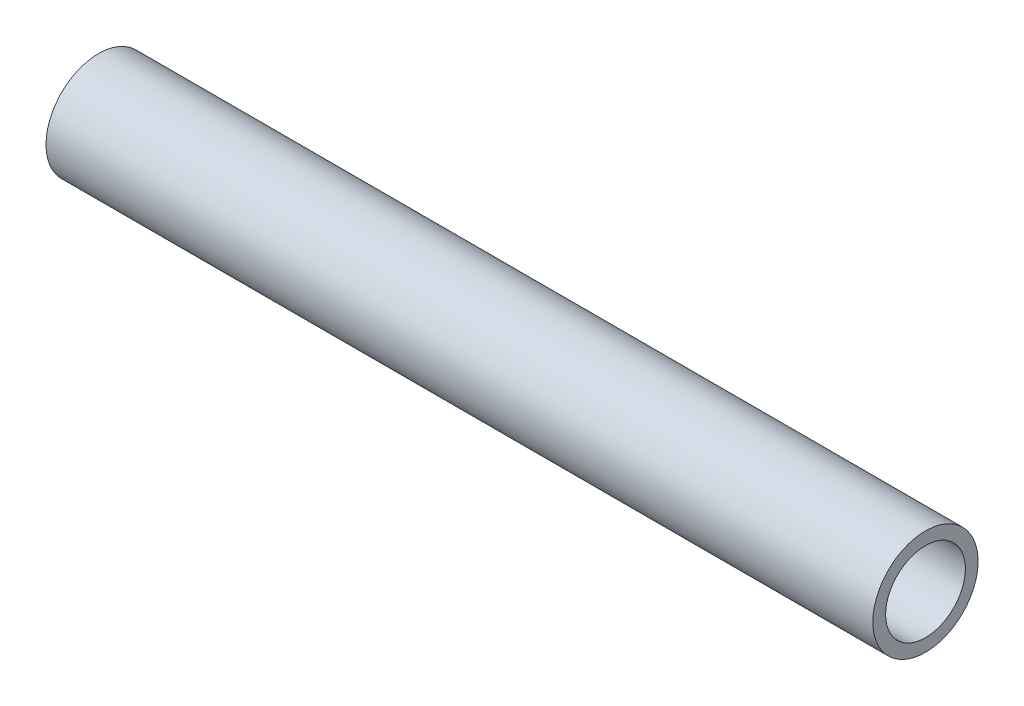
SolidWorks part; units mm, degrees
ref_plane "Płaszczyzna przednia" through (0, 0, 0) normal (0, 0, 1) x (1, 0, 0)
ref_plane "Płaszczyzna górna" through (0, 0, 0) normal (0, 1, 0) x (1, 0, 0)
ref_plane "Płaszczyzna prawa" through (0, 0, 0) normal (1, 0, 0) x (0, 0, -1)
sketch "Szkic1" plane through (0, 0, 0) normal (0, 0, 1) x (1, 0, 0)
  line L0 (0, 0) -> (154.6204, 0)
  line L1 (0, 0) -> (0, 7)
  line L2 (0, 7) -> (110, 7)
  line L3 (110, 7) -> (110, 0)
  line L4 (0, 7) -> (0, 5.3057)
  line L5 (0, 5.3057) -> (110, 5.3057)
revolve "Obrót1" add sketch "Szkic1" angle 360 about L0
